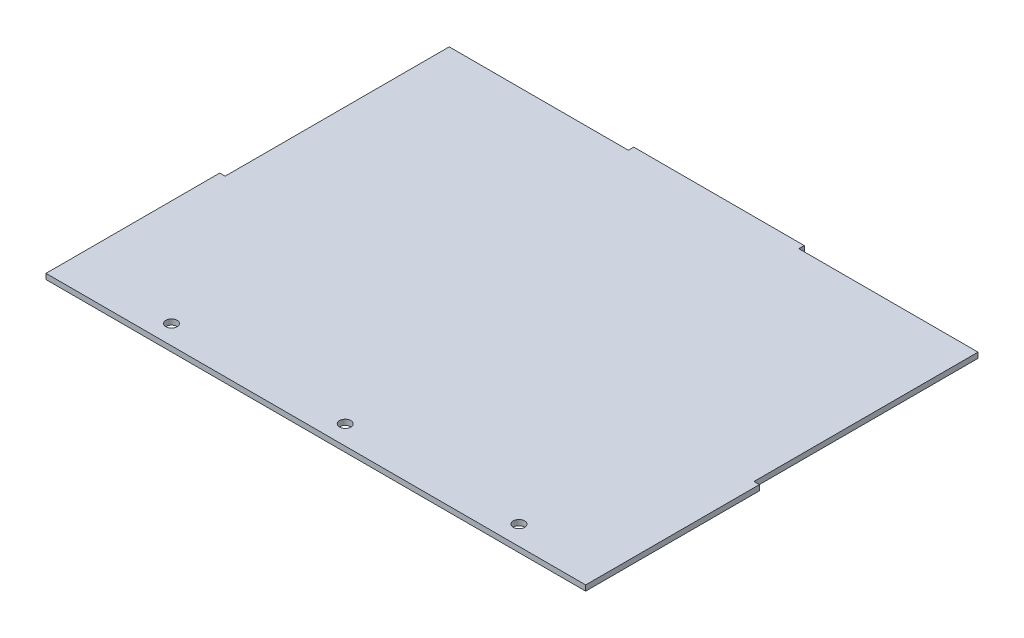
SolidWorks part; units mm, degrees
material "6061-T6 (SS)"
ref_plane "X-Y Datum" through (0, 0, 0) normal (0, 0, 1) x (1, 0, 0)
ref_plane "X-Z Datum" through (0, 0, 0) normal (0, 1, 0) x (1, 0, 0)
ref_plane "Y-Z Datum" through (0, 0, 0) normal (1, 0, 0) x (0, 0, -1)
sketch "Sketch1" plane through (0, 0, 0) normal (0, 0, 1) x (1, 0, 0)
  line L1 (-157.79, -1.5875) -> (157.79, -1.5875)
  line L2 (-157.79, -1.5875) -> (-157.79, 1.5875)
  line L3 (-157.79, 1.5875) -> (157.79, 1.5875)
  line L4 (157.79, -1.5875) -> (157.79, 1.5875)
  line L5 (-157.79, -1.5875) -> (157.79, 1.5875) construction
  line L6 (-157.79, 1.5875) -> (157.79, -1.5875) construction
  point P0 (0, 0)
  dimension "D1" = 315.58
  dimension "D2" = 3.175
extrude "Boss-Extrude1" add sketch "Sketch1" along normal blind 232.6
sketch "Sketch5" plane through (0, 1.5875, 0) normal (0, 1, 0) x (1, 0, 0)
  line L15 (-157.79, 0) -> (-154.615, 0)
  line L16 (-157.79, 0) -> (-157.79, -131)
  line L17 (-157.79, -131) -> (-154.615, -131)
  line L18 (-154.615, 0) -> (-154.615, -131)
  dimension "D3" = 3.175
  dimension "D4" = 131
extrude "Cut-Extrude2" cut sketch "Sketch5" against normal through all and the other way through all
mirror "Mirror1" about plane through (0, 0, 0) normal (1, 0, 0) of "Cut-Extrude2"
sketch "Sketch7" plane through (0, -1.5875, 0) normal (0, -1, 0) x (1, 0, 0)
  line L0 (110.4954, 221.3083) -> (104.4954, 221.3083) construction
  circle A0 centre (107.4954, 221.3083) radius 3.302
  dimension "D1" = 6.604
extrude "Cut-Extrude3" cut sketch "Sketch7" against normal through all
pattern_linear "LPattern1" count 3 spacing 101.6 along (-1, 0, 0) of "Cut-Extrude3"
sketch "Sketch10" plane through (0, 0, 0) normal (0, 0, -1) x (-1, 0, 0)
  line L0 (-154.615, -1.5875) -> (-154.615, 1.5875) construction
  line L2 (154.615, -1.5875) -> (154.615, 1.5875) construction
  line L4 (-154.615, 1.5875) -> (154.615, 1.5875) construction
  line L5 (-49.84, 1.5875) -> (49.84, 1.5875)
  line L6 (-49.84, 1.5875) -> (-49.84, -1.5875)
  line L7 (-49.84, -1.5875) -> (49.84, -1.5875)
  line L8 (49.84, 1.5875) -> (49.84, -1.5875)
  line L9 (154.615, -1.5875) -> (-154.615, -1.5875) construction
  dimension "D1" = 104.775
  dimension "D2" = 104.775
extrude "Boss-Extrude2" add sketch "Sketch10" along normal blind 3.175
